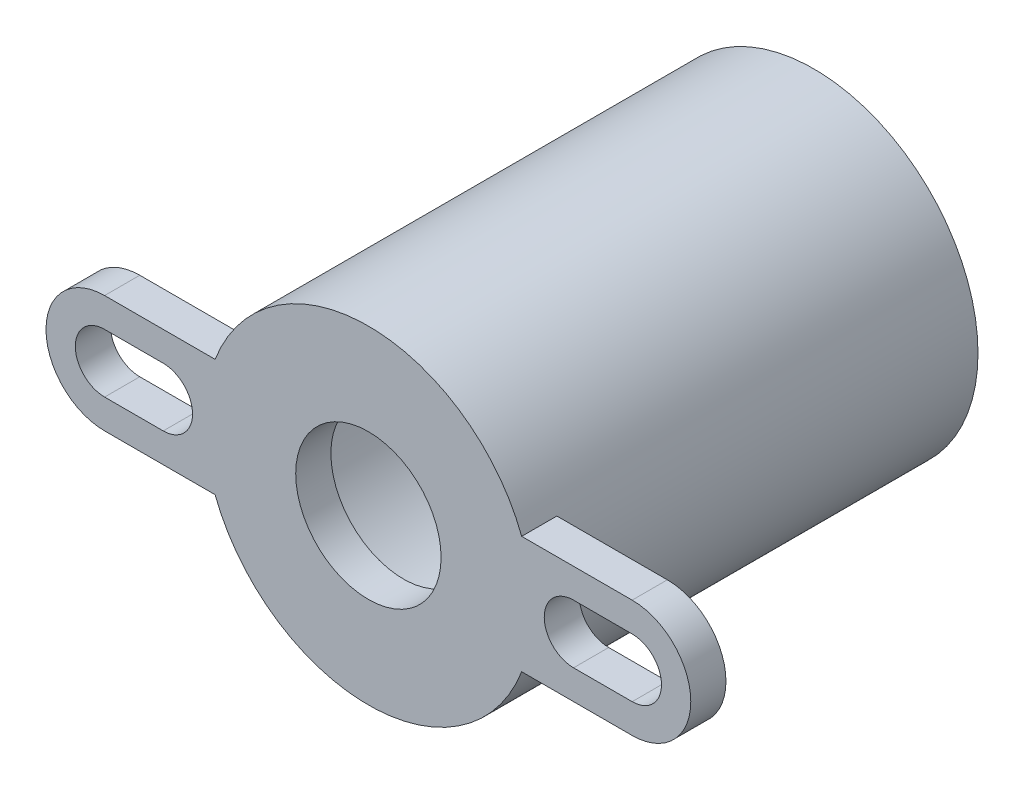
SolidWorks part; units mm, degrees
ref_plane "Alzado" through (0, 0, 0) normal (0, 0, 1) x (1, 0, 0)
ref_plane "Planta" through (0, 0, 0) normal (0, 1, 0) x (1, 0, 0)
ref_plane "Vista lateral" through (0, 0, 0) normal (1, 0, 0) x (0, 0, -1)
sketch "Sketch1" plane through (0, 0, 0) normal (0, 0, 1) x (1, 0, 0)
  line L0 (0, 0) -> (45, 0) construction
  line L1 (0, 5) -> (45, 5)
  line L2 (0, -5) -> (45, -5)
  arc A0 (0, 5) -> (0, -5) centre (0, 0) ccw
  arc A1 (45, -5) -> (45, 5) centre (45, 0) ccw
  circle A4 centre (22.5, 0) radius 14
  point P3 (22.5, 0)
  point P8 (-5, 0)
  point P9 (50, 0)
  dimension "D1" = 55
  dimension "D2" = 10
  dimension "D4" = 28
extrude "Boss-Extrude1" add sketch "Sketch1" along normal blind 3
sketch "Sketch2" plane through (0, 0, 0) normal (0, 0, -1) x (-1, 0, 0)
  circle A0 centre (-22.5, 0) radius 6.2
  arc A1 (-9.4233, 5) -> (-35.5767, 5) centre (-22.5, 0) ccw construction
  dimension "D1" = 12.4
extrude "Cut-Extrude1" cut sketch "Sketch2" against normal blind 8
sketch "Sketch3" plane through (0, 0, 0) normal (0, 0, -1) x (-1, 0, 0)
  circle A0 centre (-22.5, 0) radius 11.5
  circle A1 centre (-22.5, 0) radius 14
  arc A2 (-35.5767, -5) -> (-9.4233, -5) centre (-22.5, 0) ccw construction
  dimension "D1" = 28
  dimension "D2" = 23
extrude "Boss-Extrude2" add sketch "Sketch3" along normal blind 35
sketch "Sketch4" plane through (0, 0, 0) normal (0, 0, -1) x (-1, 0, 0)
  line L0 (-40, 0) -> (-45, 0) construction
  line L1 (-40, -2.5) -> (-45, -2.5)
  line L2 (-40, 2.5) -> (-45, 2.5)
  line L3 (-5, 0) -> (0, 0) construction
  line L4 (-5, 2.5) -> (0, 2.5)
  line L5 (-5, -2.5) -> (0, -2.5)
  arc A0 (-40, -2.5) -> (-40, 2.5) centre (-40, 0) ccw
  arc A1 (-45, 2.5) -> (-45, -2.5) centre (-45, 0) ccw
  arc A2 (-5, 2.5) -> (-5, -2.5) centre (-5, 0) ccw
  arc A3 (0, -2.5) -> (0, 2.5) centre (0, 0) ccw
  arc A4 (-45, 5) -> (-45, -5) centre (-45, 0) ccw construction
  arc A5 (0, -5) -> (0, 5) centre (0, 0) ccw construction
  point P3 (-42.5, 0)
  point P8 (-2.5, 0)
  point P21 (-7.5, 0)
  point P22 (2.5, 0)
  point P23 (-47.5, 0)
  point P24 (-37.5, 0)
  dimension "D3" = 10
  dimension "D1" = 5
  dimension "D2" = 5
  dimension "D4" = 10
extrude "Cut-Extrude2" cut sketch "Sketch4" against normal through all
